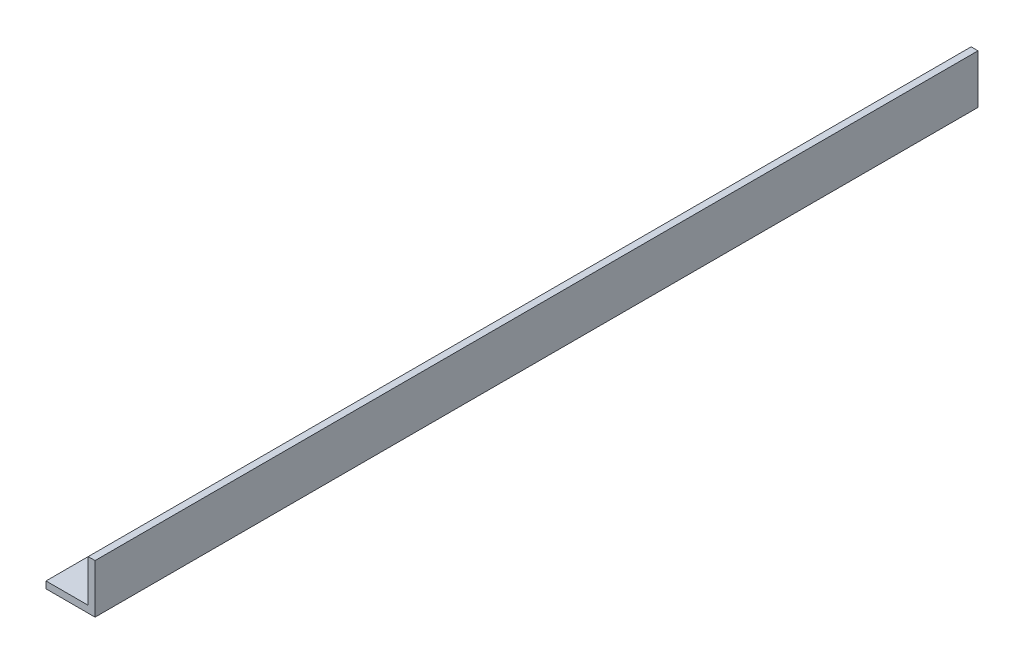
SolidWorks part; units mm, degrees
ref_plane "Front Plane" through (0, 0, 0) normal (0, 0, 1) x (1, 0, 0)
ref_plane "Top Plane" through (0, 0, 0) normal (0, 1, 0) x (1, 0, 0)
ref_plane "Right Plane" through (0, 0, 0) normal (1, 0, 0) x (0, 0, -1)
sketch "Sketch1" plane through (0, 0, 0) normal (0, 0, 1) x (1, 0, 0)
  line L0 (0, 0) -> (50, 0)
  line L1 (50, 0) -> (50, 50)
  line L2 (50, 50) -> (43, 50)
  line L3 (43, 50) -> (43, 7)
  line L4 (43, 7) -> (0, 7)
  line L5 (0, 7) -> (0, 0)
  dimension "D1" = 7
  dimension "D2" = 50
  dimension "D3" = 50
  dimension "D4" = 7
extrude "Boss-Extrude1" add sketch "Sketch1" along normal blind 900
